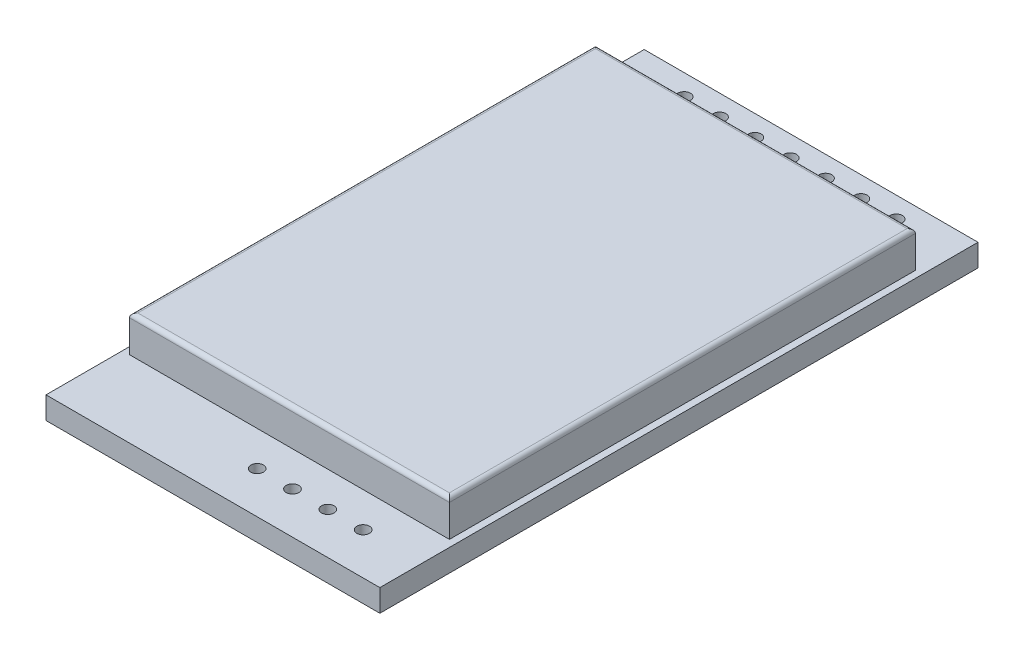
SolidWorks part; units mm, degrees
ref_plane "Ön Düzlem" through (0, 0, 0) normal (0, 0, 1) x (1, 0, 0)
ref_plane "Üst Düzlem" through (0, 0, 0) normal (0, 1, 0) x (1, 0, 0)
ref_plane "Sağ Düzlem" through (0, 0, 0) normal (1, 0, 0) x (0, 0, -1)
sketch "Sketch1" plane through (0, 0, 0) normal (0, 1, 0) x (1, 0, 0)
  line L1 (0, 0) -> (24, 0)
  line L2 (0, 0) -> (0, 43)
  line L3 (0, 43) -> (24, 43)
  line L4 (24, 0) -> (24, 43)
  circle A0 centre (19.62, 41.5) radius 0.45
  circle A1 centre (17.08, 41.5) radius 0.45
  circle A2 centre (14.54, 41.5) radius 0.45
  circle A3 centre (12, 41.5) radius 0.45
  circle A4 centre (9.46, 41.5) radius 0.45
  circle A5 centre (6.92, 41.5) radius 0.45
  circle A6 centre (4.38, 41.5) radius 0.45
  circle A7 centre (19.8, 3) radius 0.45
  circle A8 centre (17.26, 3) radius 0.45
  circle A9 centre (14.72, 3) radius 0.45
  circle A10 centre (12.18, 3) radius 0.45
  dimension "D3" = 0.9
  dimension "D13" = 0.9
  dimension "D1" = 24
  dimension "D2" = 43
  dimension "D4" = 1.5
  dimension "D5" = 4.38
  dimension "D7" = 2.54
  dimension "D8" = 2.54
  dimension "D9" = 2.54
  dimension "D10" = 2.54
  dimension "D11" = 3
  dimension "D12" = 4.2
  dimension "D6" = 7
extrude "Boss-Extrude1" add sketch "Sketch1" along normal blind 1.6
sketch "Sketch2" plane through (0, 1.6, 0) normal (0, 1, 0) x (1, 0, 0)
  line L0 (24, 0) -> (24, 43) construction
  line L5 (0.5, 39) -> (23.5, 39)
  line L6 (0.5, 39) -> (0.5, 5.5)
  line L7 (0.5, 5.5) -> (23.5, 5.5)
  line L8 (23.5, 39) -> (23.5, 5.5)
  line L9 (24, 43) -> (0, 43) construction
  dimension "D1" = 33.5
  dimension "D2" = 23
  dimension "D3" = 0.5
  dimension "D4" = 4
extrude "Boss-Extrude2" add sketch "Sketch2" along normal blind 2.6
fillet "Fillet1" radius 0.3 4 edges at (12, 4.2, -39) (23.5, 4.2, -22.25) (12, 4.2, -5.5) (0.5, 4.2, -22.25)
